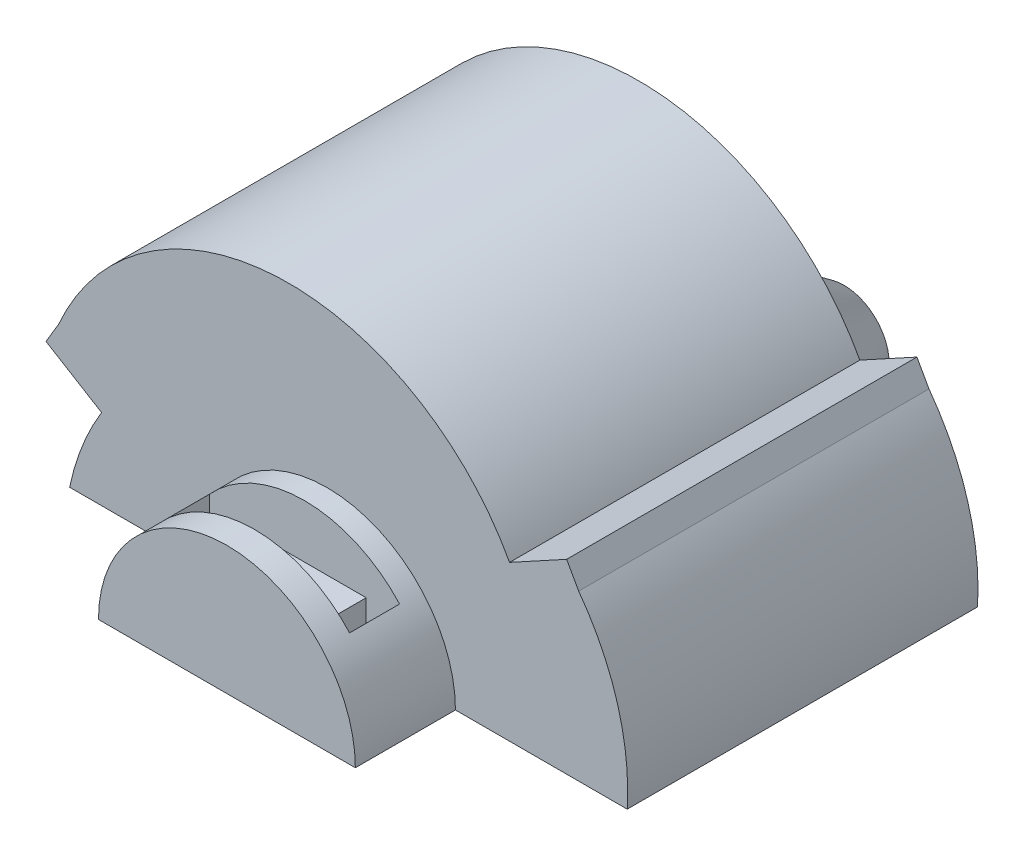
SolidWorks part; units mm, degrees
ref_plane "Alzado" through (0, 0, 0) normal (0, 0, 1) x (1, 0, 0)
ref_plane "Planta" through (0, 0, 0) normal (0, 1, 0) x (1, 0, 0)
ref_plane "Vista lateral" through (0, 0, 0) normal (1, 0, 0) x (0, 0, -1)
sketch "Croquis1" plane through (0, 0, 0) normal (0, 0, 1) x (1, 0, 0)
  line L0 (-54.5351, 31.4828) -> (-55.2579, 32.775)
  line L1 (-69.6242, 5.1176) -> (-68.6242, 5.1176)
  line L2 (-68.6242, 5.1176) -> (-68.6242, 9.1176)
  line L3 (-85.7122, 29.7526) -> (-86.47, 28.4805)
  line L4 (-83.9136, 29.8676) -> (-84.4136, 29.0016)
  line L5 (-84.4136, 29.0016) -> (-80.9495, 27.0016)
  line L6 (-86.47, 28.4805) -> (-83.1384, 26.453)
  line L7 (-55.3348, 29.8676) -> (-55.8348, 30.7337)
  line L8 (-55.8348, 30.7337) -> (-59.2989, 28.7337)
  line L9 (-55.2579, 32.775) -> (-58.6796, 30.9036)
  line L10 (-68.6253, 3.6175) -> (-67.1448, 3.5974)
  line L11 (-67.1448, 3.5974) -> (-67.0547, 7.4963)
  arc A1 (-69.6242, 5.1176) -> (-80.9495, 27.0016) centre (-70.3006, 18.6401) cw
  arc A2 (-55.3348, 29.8676) -> (-68.6242, 9.1176) centre (-66.7074, 22.5206) cw
  arc A3 (-83.9136, 29.8676) -> (-59.2989, 28.7337) centre (-71.8646, 23.6922) cw
  arc A4 (-83.1384, 26.453) -> (-68.6253, 3.6175) centre (-70.3045, 18.58) ccw
  arc A5 (-58.6796, 30.9036) -> (-85.7122, 29.7526) centre (-71.9148, 23.7256) ccw
  arc A6 (-67.0547, 7.4963) -> (-54.5351, 31.4828) centre (-66.6534, 22.5474) ccw
  point P16 (-69.6242, 21.6176)
  point P24 (-69.6242, 21.6176)
  point P33 (-69.6242, 21.6176)
  dimension "D1" = 3
  dimension "D2" = 3
  dimension "D5" = 3
extrude "Saliente-Extruir1" add sketch "Croquis1" along normal blind 18
sketch "Croquis2" plane through (0, 0, 0) normal (0, 0, -1) x (-1, 0, 0)
  line L0 (67.0547, 7.4963) -> (67.1448, 3.5974)
  line L1 (67.1448, 3.5974) -> (68.6253, 3.6175)
  line L2 (58.6796, 30.9036) -> (55.2579, 32.775)
  line L3 (55.2579, 32.775) -> (54.5351, 31.4828)
  line L4 (83.1384, 26.453) -> (86.47, 28.4805)
  line L5 (86.47, 28.4805) -> (85.7122, 29.7526)
  arc A0 (68.6253, 3.6175) -> (83.1384, 26.453) centre (70.3045, 18.58) ccw
  arc A2 (54.5351, 31.4828) -> (67.0547, 7.4963) centre (66.6534, 22.5474) ccw
  arc A3 (85.7122, 29.7526) -> (58.6796, 30.9036) centre (71.9148, 23.7256) ccw
  circle A4 centre (69.6242, 21.6176) radius 2.7
  point P26 (69.6242, 21.6176)
  dimension "D1" = 3
extrude "Saliente-Extruir2" add sketch "Croquis2" along normal blind 1.5
sketch "Croquis3" plane through (0, 0, 18) normal (0, 0, 1) x (1, 0, 0)
  line L0 (-67.1448, 3.5974) -> (-67.0547, 7.4963)
  line L2 (-67.1448, 3.5974) -> (-68.6253, 3.6175)
  line L3 (-86.47, 28.4805) -> (-83.1384, 26.453)
  line L4 (-86.47, 28.4805) -> (-85.7122, 29.7526)
  line L5 (-55.2579, 32.775) -> (-58.6796, 30.9036)
  line L6 (-55.2579, 32.775) -> (-54.5351, 31.4828)
  arc A0 (-68.6253, 3.6175) -> (-83.1384, 26.453) centre (-70.3045, 18.58) cw
  arc A2 (-85.7122, 29.7526) -> (-58.6796, 30.9036) centre (-71.9148, 23.7256) cw
  arc A3 (-54.5351, 31.4828) -> (-67.0547, 7.4963) centre (-66.6534, 22.5474) cw
  dimension "D1" = 3
extrude "Saliente-Extruir3" add sketch "Croquis3" along normal blind 1.5
sketch "Croquis6" plane through (0, 0, -1.5) normal (0, 0, -1) x (-1, 0, 0)
  line L1 (72.3242, 21.6176) -> (66.9242, 21.6176)
  line L2 (72.3242, 21.6176) -> (72.3242, 20.4357)
  line L3 (72.3242, 20.4357) -> (66.9242, 20.4357)
  line L4 (66.9242, 21.6176) -> (66.9242, 20.4357)
  circle A0 centre (69.6242, 21.6176) radius 2.7 construction
extrude "Saliente-Extruir7" add sketch "Croquis6" along normal blind 10
ref_plane "Plano2" through (0, 21.6176, 0) normal (0, 1, 0) x (1, 0, 0)
sketch "Croquis7" plane through (0, 21.6176, 0) normal (0, 1, 0) x (1, 0, 0)
  line L1 (-72.3242, 11.5) -> (-66.9242, 11.5)
  line L2 (-72.3242, 11.5) -> (-72.3242, 1.5)
  line L3 (-72.3242, 1.5) -> (-66.9242, 1.5)
  line L4 (-66.9242, 11.5) -> (-66.9242, 1.5)
extrude "Cortar-Extruir2" cut sketch "Croquis7" against normal up to vertex (16.5 mm away)
sketch "Croquis8" plane through (0, 21.6176, 0) normal (0, 1, 0) x (1, 0, 0)
  line L0 (-72.3242, 1.5) -> (-79.4868, 1.5)
  line L1 (-72.3242, 1.5) -> (-72.3242, 11.5)
  line L2 (-79.4868, 1.5) -> (-72.3242, 11.5)
  line L6 (-72.3242, -19.5) -> (-69.6242, -19.5)
  line L7 (-69.6242, -19.5) -> (-69.6242, -25.5)
  line L8 (-69.6242, -25.5) -> (-72.3242, -25.5)
  line L9 (-77.3242, -25.5) -> (-77.3242, -19.5)
  line L10 (-72.3242, -25.5) -> (-77.3242, -25.5)
  line L11 (-77.3242, -19.5) -> (-72.3242, -19.5)
  dimension "D5" = 21
revolve "Revolución1" add sketch "Croquis8" angle 360 about L7
sketch "Croquis9" plane through (0, 21.6176, 0) normal (0, 1, 0) x (1, 0, 0)
  line L1 (-87.9437, -36.577) -> (-35.4756, -36.577)
  line L2 (-87.9437, -36.577) -> (-87.9437, 19.1063)
  line L3 (-87.9437, 19.1063) -> (-35.4756, 19.1063)
  line L4 (-35.4756, -36.577) -> (-35.4756, 19.1063)
extrude "Cortar-Extruir3" cut sketch "Croquis9" against normal blind 30
sketch "Croquis10" plane through (0, 21.6176, 0) normal (0, -1, 0) x (1, 0, 0)
  line L1 (-63.9242, -5.5) -> (-65.9242, -5.5)
  line L2 (-63.9242, -5.5) -> (-63.9242, -2.5)
  line L3 (-63.9242, -2.5) -> (-65.9242, -2.5)
  line L4 (-65.9242, -5.5) -> (-65.9242, -2.5)
  line L5 (-66.9242, -11.5) -> (-66.9242, 0) construction
  line L6 (-51.6257, -1.5) -> (-59.7617, -1.5) construction
  line L7 (-72.3242, 0) -> (-72.3242, -11.5) construction
  line L8 (-73.3242, -5.5) -> (-75.3242, -5.5)
  line L9 (-73.3242, -5.5) -> (-73.3242, -2.5)
  line L10 (-73.3242, -2.5) -> (-75.3242, -2.5)
  line L11 (-75.3242, -5.5) -> (-75.3242, -2.5)
  line L13 (-63.9242, 20.85) -> (-65.9242, 20.85)
  line L14 (-63.9242, 20.85) -> (-63.9242, 23.8458)
  line L15 (-63.9242, 23.8458) -> (-65.9242, 23.8458)
  line L16 (-65.9242, 20.85) -> (-65.9242, 23.8458)
  line L17 (-73.3242, 20.85) -> (-75.3242, 20.85)
  line L18 (-73.3242, 20.85) -> (-73.3242, 23.8458)
  line L19 (-73.3242, 23.8458) -> (-75.3242, 23.8458)
  line L20 (-75.3242, 20.85) -> (-75.3242, 23.8458)
  dimension "D1" = 3
  dimension "D2" = 2
  dimension "D3" = 1
  dimension "D4" = 1
  dimension "D5" = 2
  dimension "D6" = 1
  dimension "D7" = 23.35
  dimension "D8" = 23.35
extrude "Cortar-Extruir4" cut sketch "Croquis10" against normal blind 10
sketch "Croquis11" plane through (-73.3242, 0, 0) normal (-1, 0, 0) x (0, 0, 1)
  line L0 (23.8458, 28.3704) -> (23.8458, 21.6176) construction
  line L1 (23.8458, 26.1211) -> (20.85, 26.1211)
  line L2 (23.8458, 26.1211) -> (23.8458, 32.4082)
  line L3 (23.8458, 32.4082) -> (20.85, 32.4082)
  line L4 (20.85, 26.1211) -> (20.85, 32.4082)
  line L5 (-2.5, 29.9822) -> (-2.5, 21.6176) construction
  line L6 (-2.5, 27.1856) -> (-5.5, 27.1856)
  line L7 (-2.5, 27.1856) -> (-2.5, 33.5847)
  line L8 (-2.5, 33.5847) -> (-5.5, 33.5847)
  line L9 (-5.5, 27.1856) -> (-5.5, 33.5847)
extrude "Cortar-Extruir5" cut sketch "Croquis11" against normal up to vertex (7.4 mm away)
sketch "Croquis12" plane through (0, 21.6176, 0) normal (0, -1, 0) x (1, 0, 0)
  line L1 (-69.6242, 18) -> (-69.6242, 15)
  line L3 (-53.1982, 18) -> (-83.5085, 18) construction
  line L4 (-69.6242, 18) -> (-73.3242, 18)
  line L5 (-73.3242, 18) -> (-73.3242, 15)
  line L6 (-73.3242, 15) -> (-69.6242, 15)
revolve "Revolución2" add sketch "Croquis12" angle 180 about L1
